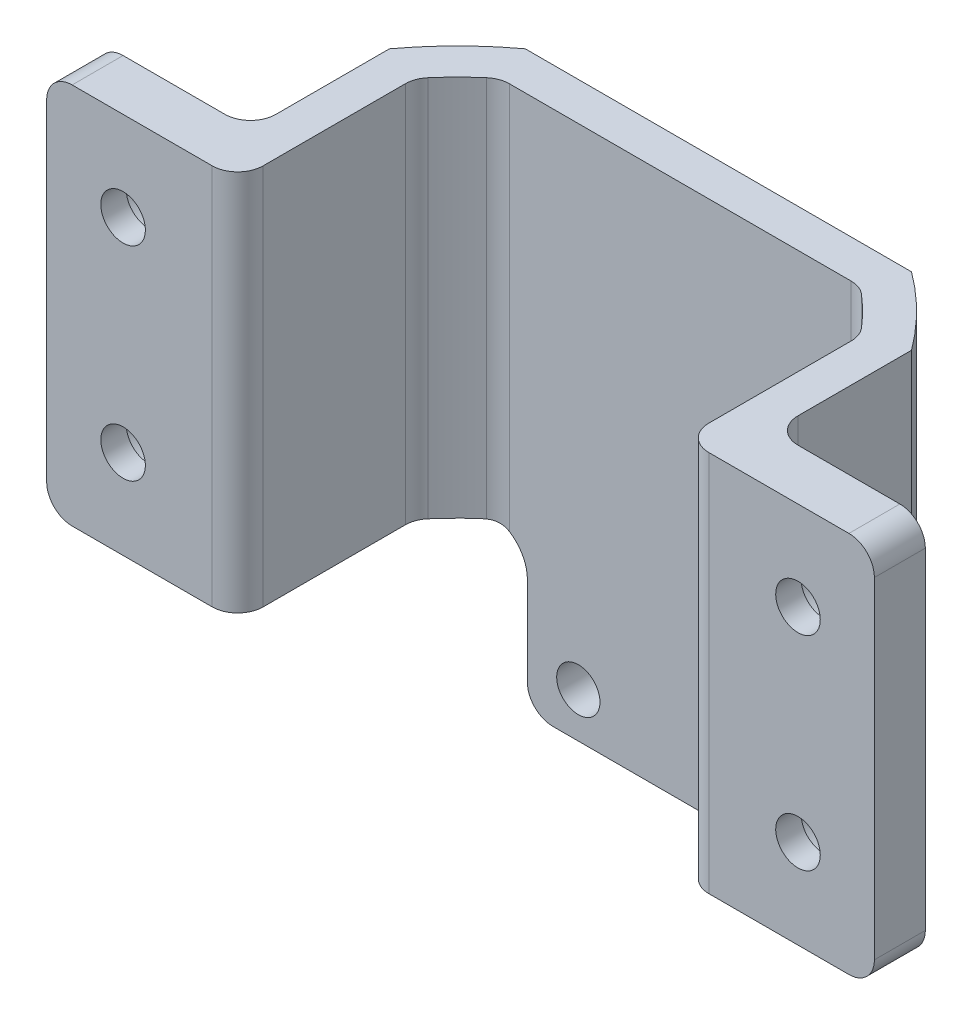
SolidWorks part; units mm, degrees
ref_plane "前视基准面" through (0, 0, 0) normal (0, 0, 1) x (1, 0, 0)
ref_plane "上视基准面" through (0, 0, 0) normal (0, 1, 0) x (1, 0, 0)
ref_plane "右视基准面" through (0, 0, 0) normal (1, 0, 0) x (0, 0, -1)
other "Configuration Table"
sketch "草图1" plane through (0, 0, 0) normal (0, 1, 0) x (1, 0, 0)
  line L0 (-17.5, 14.1421) -> (-17.5, -14.1421)
  line L1 (-17.5, 17.5) -> (17.5, 17.5) construction
  line L2 (-17.5, 17.5) -> (-17.5, -17.5) construction
  line L3 (-17.5, -17.5) -> (17.5, -17.5) construction
  line L4 (17.5, 17.5) -> (17.5, -17.5) construction
  line L5 (-17.5, 17.5) -> (17.5, -17.5) construction
  line L6 (-17.5, -17.5) -> (17.5, 17.5) construction
  line L11 (15.1658, 20.5) -> (-15.1658, 20.5)
  line L12 (-20.5, 15.1658) -> (-20.5, -15.1658)
  line L13 (-14.1421, -17.5) -> (14.1421, -17.5)
  line L14 (17.5, -14.1421) -> (17.5, 14.1421)
  line L15 (14.1421, 17.5) -> (-14.1421, 17.5)
  line L16 (-15.1658, -20.5) -> (15.1658, -20.5)
  line L17 (20.5, -15.1658) -> (20.5, 15.1658)
  arc A0 (-14.1421, 17.5) -> (-17.5, 14.1421) centre (0, 0) ccw
  arc A1 (-17.5, -14.1421) -> (-14.1421, -17.5) centre (0, 0) ccw
  arc A2 (14.1421, -17.5) -> (17.5, -14.1421) centre (0, 0) ccw
  arc A3 (17.5, 14.1421) -> (14.1421, 17.5) centre (0, 0) ccw
  arc A4 (-15.1658, 20.5) -> (-20.5, 15.1658) centre (0, 0) ccw
  arc A5 (-20.5, -15.1658) -> (-15.1658, -20.5) centre (0, 0) ccw
  arc A6 (15.1658, -20.5) -> (20.5, -15.1658) centre (0, 0) ccw
  arc A7 (20.5, 15.1658) -> (15.1658, 20.5) centre (0, 0) ccw
  point P0 (0, 0)
  point P6 (0, 0)
  dimension "D5" = 45
  dimension "D1" = 35
  dimension "D2" = 35
  dimension "D3" = 3
extrude "凸台-拉伸1" add sketch "草图1" along normal blind 30
fillet "圆角1" radius 2 8 edges at (17.5, 15, -14.1421) (14.1421, 15, -17.5) (17.5, 15, 14.1421) (14.1421, 15, 17.5) (-14.1421, 15, 17.5) (-17.5, 15, 14.1421) (-17.5, 15, -14.1421) (-14.1421, 15, -17.5)
ref_plane "基准面1" through (0, 0, 0) normal (-1, 0, 0) x (0, 0, 1)
sketch "草图2" plane through (-20.5, 0, 0) normal (-1, 0, 0) x (0, 0, 1)
  line L1 (-0.25, 30) -> (-4.25, 30)
  line L2 (-0.25, 30) -> (-0.25, 0)
  line L3 (-0.25, 0) -> (-4.25, 0)
  line L4 (-4.25, 30) -> (-4.25, 0)
  line L5 (-15.1658, 0) -> (15.1658, 0) construction
  line L6 (-15.1658, 30) -> (15.1658, 30) construction
  line L7 (0, 30) -> (0, 0) construction
  dimension "D1" = 4
  dimension "D2" = 0.5
extrude "凸台-拉伸2" add sketch "草图2" along normal blind 12
sketch "草图3" plane through (0, 0, -0.25) normal (0, 0, 1) x (1, 0, 0)
  line L1 (-45.3491, 49.7736) -> (34.0354, 49.7736)
  line L2 (-45.3491, 49.7736) -> (-45.3491, -10.9658)
  line L3 (-45.3491, -10.9658) -> (34.0354, -10.9658)
  line L4 (34.0354, 49.7736) -> (34.0354, -10.9658)
extrude "切除-拉伸1" cut sketch "草图3" along normal blind 30
sketch "草图4" plane through (0, 0, -4.25) normal (0, 0, -1) x (-1, 0, 0)
  line L0 (20.5, 15) -> (32.5, 15) construction
  line L1 (20.5, 30) -> (20.5, 0) construction
  line L2 (32.5, 30) -> (32.5, 0) construction
  circle A0 centre (26.5, 23) radius 1.75
  circle A1 centre (26.5, 7) radius 1.75
  dimension "D1" = 3.5
  dimension "D2" = 8
  dimension "D3" = 6
extrude "切除-拉伸2" cut sketch "草图4" against normal blind 30
sketch "草图5" plane through (0, 0, -4.25) normal (0, 0, -1) x (-1, 0, 0)
  circle A0 centre (26.5, 23) radius 3
  circle A1 centre (26.5, 7) radius 3
  dimension "D1" = 6
  dimension "D2" = 6
extrude "切除-拉伸3" cut sketch "草图5" against normal blind 2
mirror "镜向1" about plane through (0, 0, 0) normal (-1, 0, 0) of "切除-拉伸3", "切除-拉伸2", "切除-拉伸1", "凸台-拉伸2"
fillet "圆角2" radius 2 8 edges at (32.5, 0, -2.25) (32.5, 30, -2.25) (-32.5, 30, -2.25) (-32.5, 0, -2.25) (-20.5, 15, -4.25) (-17.5, 15, -0.25) (17.5, 15, -0.25) (20.5, 15, -4.25)
sketch "草图6" plane through (0, 0, 0) normal (0, 1, 0) x (1, 0, 0)
  line L0 (15.1658, 20.5) -> (-15.1658, 20.5) construction
  line L1 (-12, 20.5) -> (12, 20.5)
  line L2 (-12, 20.5) -> (-12, 17.5)
  line L3 (-12, 17.5) -> (12, 17.5)
  line L4 (12, 20.5) -> (12, 17.5)
  line L5 (13.4164, 17.5) -> (-13.4164, 17.5) construction
  line L6 (0, 20.5) -> (0, 0) construction
  point P11 (0, 20.5)
  dimension "D1" = 24
extrude "凸台-拉伸4" add sketch "草图6" against normal blind 12
sketch "草图7" plane through (0, 0, -20.5) normal (0, 0, -1) x (-1, 0, 0)
  line L0 (0, 30) -> (0, -12) construction
  line L1 (-15.1658, 30) -> (15.1658, 30) construction
  line L2 (-12, -12) -> (12, -12) construction
  circle A0 centre (8, -8.5) radius 1.7
  circle A1 centre (-8, -8.5) radius 1.7
  dimension "D1" = 3.4
  dimension "D2" = 8
  dimension "D3" = 3.5
extrude "切除-拉伸4" cut sketch "草图7" against normal blind 12
fillet "圆角3" radius 3 6 edges at (-12.7082, 0, -17.5) (-12, 0, -19) (12, 0, -19) (12.7082, 0, -17.5) (14.1148, 0, -17.3741) (-14.1148, 0, -17.3741)
fillet "圆角4" radius 2 2 edges at (12, -12, -19) (-12, -12, -19)
